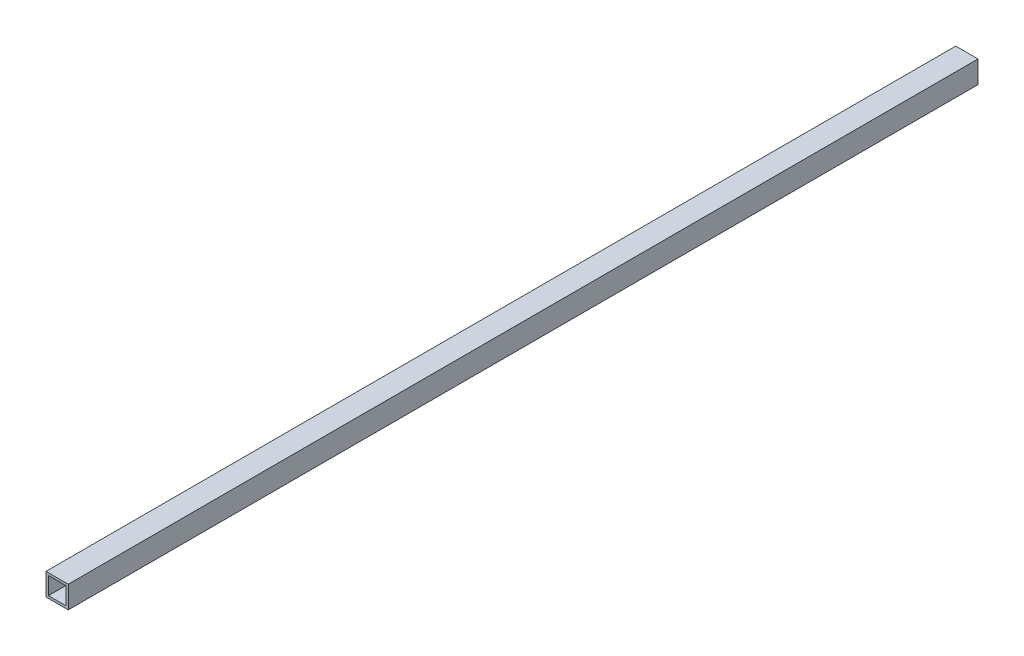
SolidWorks part; units mm, degrees
ref_plane "前视基准面" through (0, 0, 0) normal (0, 0, 1) x (1, 0, 0)
ref_plane "上视基准面" through (0, 0, 0) normal (0, 1, 0) x (1, 0, 0)
ref_plane "右视基准面" through (0, 0, 0) normal (1, 0, 0) x (0, 0, -1)
sketch "草图1" plane through (0, 0, 0) normal (0, 0, 1) x (1, 0, 0)
  line L1 (-5.5, 5.5) -> (5.5, 5.5)
  line L2 (-5.5, 5.5) -> (-5.5, -5.5)
  line L3 (-5.5, -5.5) -> (5.5, -5.5)
  line L4 (5.5, 5.5) -> (5.5, -5.5)
  line L5 (-5.5, 5.5) -> (5.5, -5.5) construction
  line L6 (-5.5, -5.5) -> (5.5, 5.5) construction
  point P0 (0, 0)
  dimension "D1" = 11
extrude "拉伸-薄壁1" add sketch "草图1" along normal blind 572 thin thin type one direction wall 1.5
